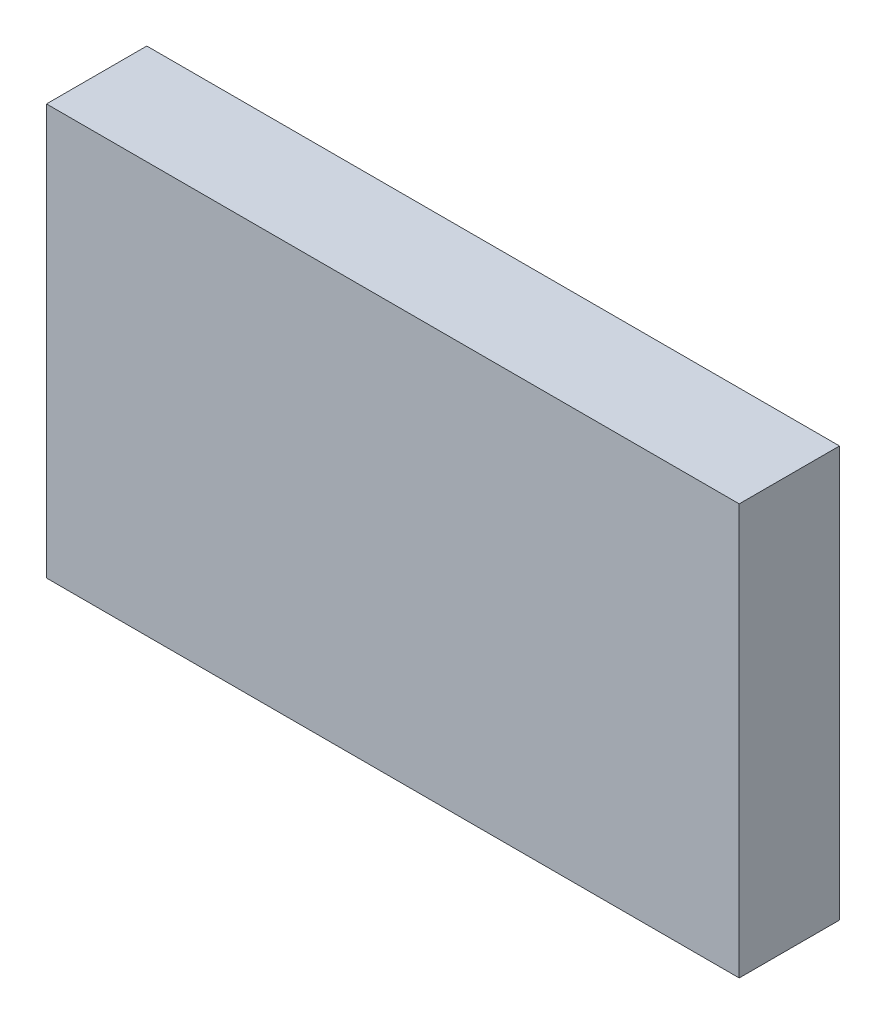
SolidWorks part; units mm, degrees
ref_plane "Alzado" through (0, 0, 0) normal (0, 0, 1) x (1, 0, 0)
ref_plane "Planta" through (0, 0, 0) normal (0, 1, 0) x (1, 0, 0)
ref_plane "Vista lateral" through (0, 0, 0) normal (1, 0, 0) x (0, 0, -1)
sketch "Croquis1" plane through (0, 0, 0) normal (0, 0, 1) x (1, 0, 0)
  line L1 (-11.05, -6.55) -> (11.05, -6.55)
  line L2 (-11.05, -6.55) -> (-11.05, 6.55)
  line L3 (-11.05, 6.55) -> (11.05, 6.55)
  line L4 (11.05, -6.55) -> (11.05, 6.55)
  line L5 (-11.05, -6.55) -> (11.05, 6.55) construction
  line L6 (-11.05, 6.55) -> (11.05, -6.55) construction
  point P0 (0, 0)
  dimension "D1" = 22.1
  dimension "D2" = 13.1
extrude "Saliente-Extruir1" add sketch "Croquis1" along normal blind 3.2
